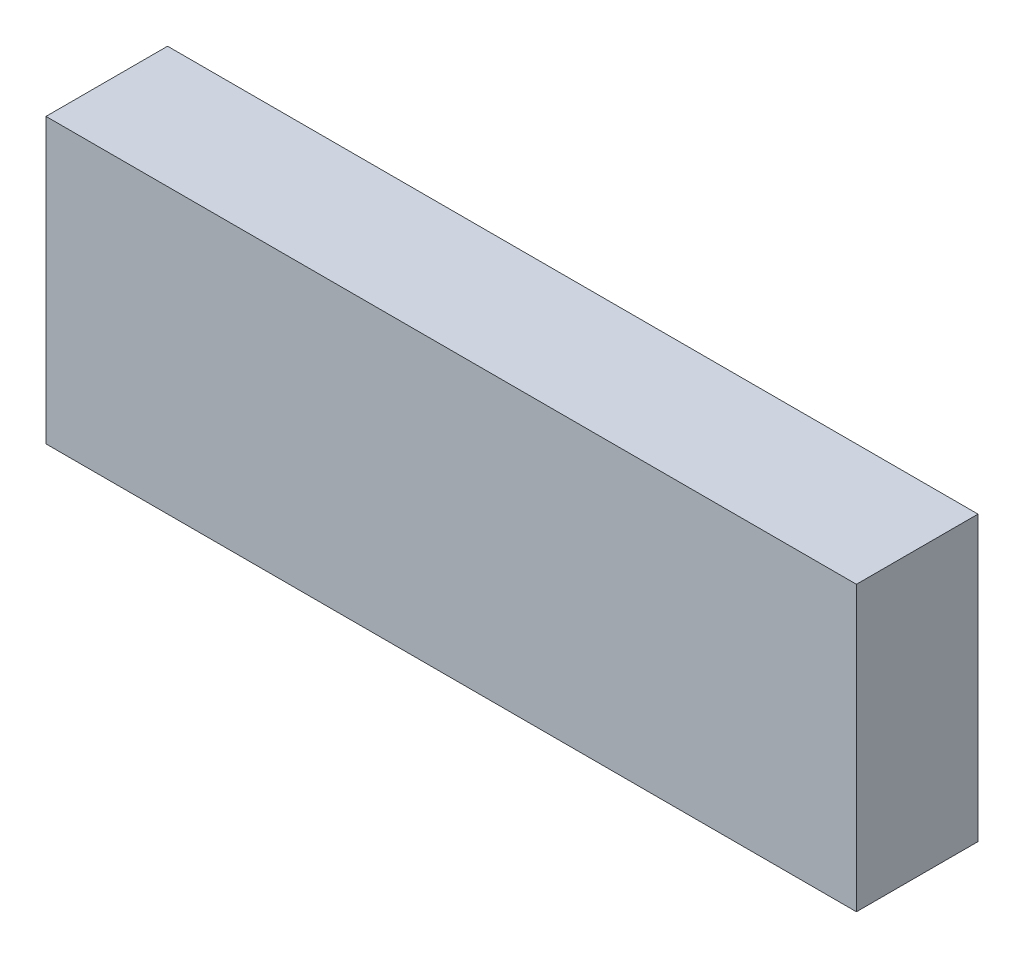
SolidWorks part; units mm, degrees
material "Oak"
ref_plane "Front" through (0, 0, 0) normal (0, 0, 1) x (1, 0, 0)
ref_plane "Top" through (0, 0, 0) normal (0, 1, 0) x (1, 0, 0)
ref_plane "Right" through (0, 0, 0) normal (1, 0, 0) x (0, 0, -1)
sketch "Sketch1" plane through (0, 0, 0) normal (0, 0, 1) x (1, 0, 0)
  line L1 (0, 0) -> (254, 0)
  line L2 (0, 0) -> (0, 88.9)
  line L3 (0, 88.9) -> (254, 88.9)
  line L4 (254, 0) -> (254, 88.9)
  dimension "D1" = 254
  dimension "D2" = 88.9
extrude "Boss-Extrude1" add sketch "Sketch1" along normal blind 38.1
